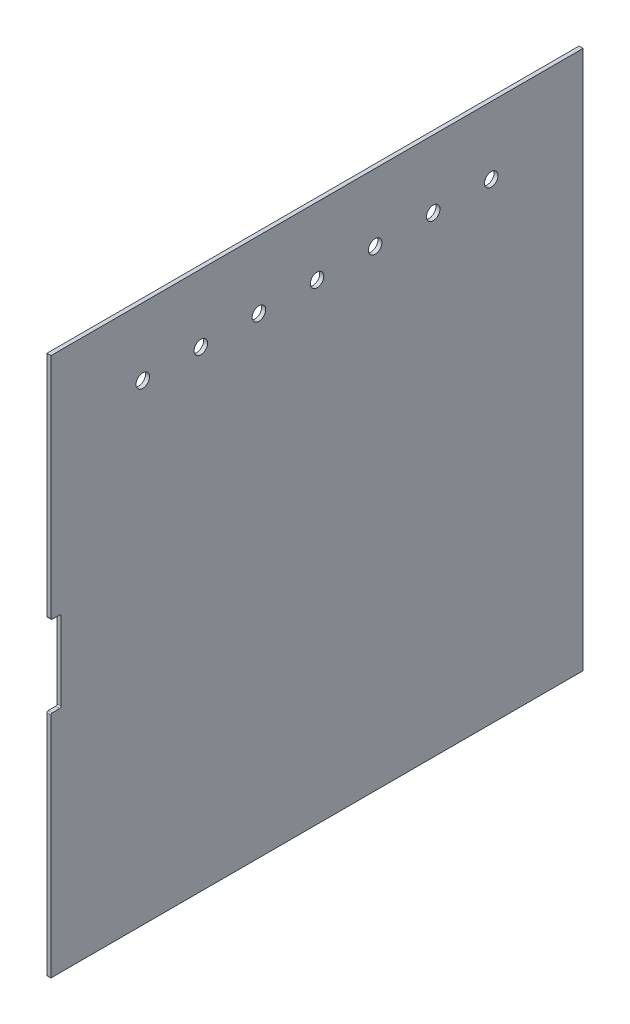
SolidWorks part; units mm, degrees
ref_plane "前基準面" through (0, 0, 0) normal (0, 0, 1) x (1, 0, 0)
ref_plane "上基準面" through (0, 0, 0) normal (0, 1, 0) x (1, 0, 0)
ref_plane "右基準面" through (0, 0, 0) normal (1, 0, 0) x (0, 0, -1)
sketch "草圖1" plane through (0, 0, 0) normal (1, 0, 0) x (0, 0, -1)
  line L1 (-197, 199.5) -> (197, 199.5)
  line L2 (-197, 199.5) -> (-197, -199.5)
  line L3 (-197, -199.5) -> (197, -199.5)
  line L4 (197, 199.5) -> (197, -199.5)
  line L5 (-197, 199.5) -> (197, -199.5) construction
  line L6 (-197, -199.5) -> (197, 199.5) construction
  point P0 (0, 0)
  dimension "D1" = 399
  dimension "398" = 394
extrude "填料-伸長1" add sketch "草圖1" along normal blind 3
sketch "草圖2" plane through (3, 0, 0) normal (1, 0, 0) x (0, 0, -1)
  line L0 (-197, 199.5) -> (-197, -199.5) construction
  line L1 (-197, 30) -> (-189.5, 30)
  line L2 (-197, 30) -> (-197, -30)
  line L3 (-197, -30) -> (-189.5, -30)
  line L4 (-189.5, 30) -> (-189.5, -30)
  line L5 (1.65, 0) -> (-1.65, 0) construction
  line L6 (197, 199.5) -> (-197, 199.5) construction
  line L7 (0, 1.65) -> (0, -1.65) construction
  circle A0 centre (-129, 149.5) radius 5
  circle A1 centre (-86, 149.5) radius 5
  circle A2 centre (-43, 149.5) radius 5
  circle A3 centre (0, 149.5) radius 5
  circle A4 centre (43, 149.5) radius 5
  circle A5 centre (86, 149.5) radius 5
  circle A6 centre (129, 149.5) radius 5
  dimension "D4" = 10
  dimension "D5" = 50
  dimension "D6" = 68
  dimension "D1" = 7.5
  dimension "D2" = 60
  dimension "D3" = 30
  dimension "D7" = 129
  dimension "D8" = 7
extrude "除料-伸長1" cut sketch "草圖2" against normal through all
fillet "圓角1" radius 1 4 edges at (1.5, -30, 197) (1.5, -30, 189.5) (1.5, 30, 197) (1.5, 30, 189.5)
